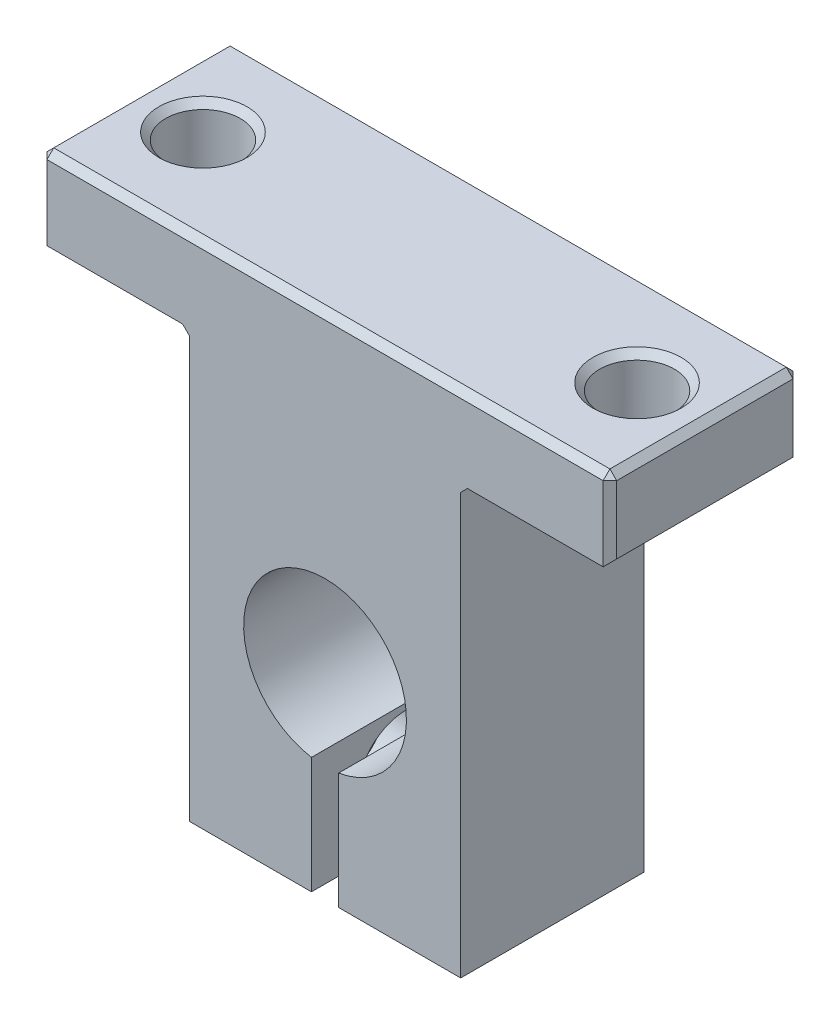
SolidWorks part; units mm, degrees
material "6061-T6 (SS)"
ref_plane "Front Plane" through (0, 0, 0) normal (0, 0, 1) x (1, 0, 0)
ref_plane "Top Plane" through (0, 0, 0) normal (0, 1, 0) x (1, 0, 0)
ref_plane "Right Plane" through (0, 0, 0) normal (1, 0, 0) x (0, 0, -1)
ref_plane "Plane1" through (0, 0, 3) normal (0, 0, -1) x (-1, 0, 0)
sketch "Sketch1" plane through (0, 0, 3) normal (0, 0, -1) x (-1, 0, 0)
  line L0 (-42, -20) -> (-42, -57.5)
  line L1 (-42, -57.5) -> (0, -57.5)
  line L2 (0, -57.5) -> (0, -20)
  line L3 (0, -20) -> (-42, -20)
extrude "Boss-Extrude1" add sketch "Sketch1" against normal blind 14
sketch "Sketch2" plane through (0, 0, 17) normal (0, 0, 1) x (1, 0, 0)
  line L0 (31, -26.5) -> (31, -57.5)
  line L1 (31, -57.5) -> (42, -57.5)
  line L2 (42, -57.5) -> (42, -26)
  line L3 (42, -26) -> (31.5, -26)
  line L4 (31.5, -26) -> (31, -26.5)
extrude "Cut-Extrude1" cut sketch "Sketch2" against normal through all
sketch "Sketch3" plane through (0, 0, 17) normal (0, 0, 1) x (1, 0, 0)
  line L0 (20, -57.5) -> (22, -57.5)
  line L1 (22, -57.5) -> (22, -48.9161)
  line L2 (20, -48.9161) -> (20, -57.5)
  arc A0 (22, -48.9161) -> (20, -48.9161) centre (21, -43) cw
extrude "Cut-Extrude2" cut sketch "Sketch3" against normal through all
sketch "Sketch4" plane through (0, 0, 17) normal (0, 0, 1) x (1, 0, 0)
  line L0 (11, -26.5) -> (10.5, -26)
  line L1 (10.5, -26) -> (0, -26)
  line L2 (0, -26) -> (0, -57.5)
  line L3 (0, -57.5) -> (11, -57.5)
  line L4 (11, -57.5) -> (11, -26.5)
extrude "Cut-Extrude3" cut sketch "Sketch4" against normal through all
hole_wizard "Ø7.3 (7.3) Diameter Hole1" positions "Sketch6" profile "Sketch5" hole size "Ø7.3" standard "ANSI Metric"
sketch "Sketch6" plane through (11, 0, 0) normal (-1, 0, 0) x (0, 0, 1)
  point P0 (10, -53.0279)
sketch "Sketch5" plane through (11, -53.0279, 10) normal (0, 1, 0) x (0, 0, 1)
  line L0 (0, 0) -> (0, 9)
  line L1 (0, 9) -> (3.65, 9)
  line L2 (3.65, 9) -> (3.65, 0)
  line L5 (3.65, 0) -> (0, 0)
  line L11 (0, -6.35) -> (0, 107.95) construction
  dimension "Thru Hole Dia." = 7.3
  dimension "Thru Hole Depth" = 9
ref_plane "Plane2" through (15, 0, 0) normal (1, 0, 0) x (0, 0, -1)
sketch "Sketch7" plane through (15, 0, 0) normal (1, 0, 0) x (0, 0, -1)
  circle A0 centre (-10, -53.0279) radius 3.5
extrude "Boss-Extrude2" add sketch "Sketch7" against normal blind 4
sketch "Sketch8" plane through (11, 0, 0) normal (-1, 0, 0) x (0, 0, 1)
  line L0 (11.4057, -54.1085) -> (11.6387, -52.3508)
  line L1 (11.6387, -52.3508) -> (10.233, -51.2702)
  line L2 (10.233, -51.2702) -> (8.5943, -51.9472)
  line L3 (8.5943, -51.9472) -> (8.3613, -53.7049)
  line L4 (8.3613, -53.7049) -> (9.767, -54.7855)
  line L5 (9.767, -54.7855) -> (11.4057, -54.1085)
extrude "Cut-Extrude4" cut sketch "Sketch8" against normal blind 2
ref_plane "Plane3" through (0, -43, 0) normal (0, 1, 0) x (1, 0, 0)
sketch "Sketch9" plane through (0, -43, 0) normal (0, 1, 0) x (1, 0, 0)
  line L0 (27, -3) -> (21, -3)
  line L1 (21, -3) -> (21, -17)
  line L2 (21, -17) -> (27, -17)
  line L3 (27, -17) -> (27, -3)
  line L4 (21, -3) -> (21, -17) construction
revolve "Cut-Revolve1" cut sketch "Sketch9" angle 360 about L4
ref_plane "Plane4" through (0, 0, 10) normal (0, 0, 1) x (1, 0, 0)
sketch "Sketch10" plane through (0, 0, 10) normal (0, 0, 1) x (1, 0, 0)
  line L0 (13, -51.4924) -> (13, -53.0279)
  line L1 (13, -53.0279) -> (13.8865, -53.0279)
  line L2 (13.8865, -53.0279) -> (13, -51.4924)
  line L3 (13, -53.0279) -> (13.8866, -53.0279) construction
revolve "Cut-Revolve2" cut sketch "Sketch10" angle 360 about L3
ref_plane "Plane5" through (0, 0, 10) normal (0, 0, -1) x (-1, 0, 0)
sketch "Sketch11" plane through (0, 0, 10) normal (0, 0, -1) x (-1, 0, 0)
  line L0 (-22, -51.0279) -> (-22, -53.0279)
  line L1 (-22, -53.0279) -> (-20, -53.0279)
  line L2 (-20, -53.0279) -> (-20, -51.0279)
  line L3 (-20, -51.0279) -> (-22, -51.0279)
  line L4 (-22, -53.0279) -> (-20, -53.0279) construction
revolve "Revolve1" add sketch "Sketch11" angle 360 about L4
hole_wizard "Ø5.5 (5.5) Diameter Hole1" positions "Sketch13" profile "Sketch12" hole size "Ø5.5" standard "ANSI Metric"
sketch "Sketch13" plane through (0, -20, 0) normal (0, 1, 0) x (1, 0, 0)
  point P0 (37, -10)
  point P1 (5, -10)
sketch "Sketch12" plane through (37, -20, 10) normal (1, 0, 0) x (0, 0, 1)
  line L0 (0, 0) -> (0, 6)
  line L1 (0, 6) -> (2.75, 6)
  line L2 (2.75, 6) -> (2.75, 0)
  line L5 (2.75, 0) -> (0, 0)
  line L11 (0, -6.35) -> (0, 107.95) construction
  dimension "Thru Hole Dia." = 5.5
  dimension "Thru Hole Depth" = 6
chamfer "Chamfer1" distance 0.5 angle 45 25 edges at (21, -20, 3) (42, -20, 10) (42, -23, 3) (21, -20, 17) (0, -20, 10) (0, -23, 3) (42, -23, 17) (42, -26, 10) (36.75, -26, 3) (31.25, -26.25, 3) (31, -42, 3) (0, -23, 17) (0, -26, 10) (5.25, -26, 3) (10.75, -26.25, 3) (11, -42, 3) (26.5, -57.5, 3) (15.5, -57.5, 3) (22, -53.208, 3) (21, -37, 3) (20, -53.208, 3) (2.25, -26, 10) (34.25, -26, 10) (37, -20, 12.75) (5, -20, 12.75)
fillet "Fillet1" radius 0.2 1 edges at (11, -53.0279, 13.5)
